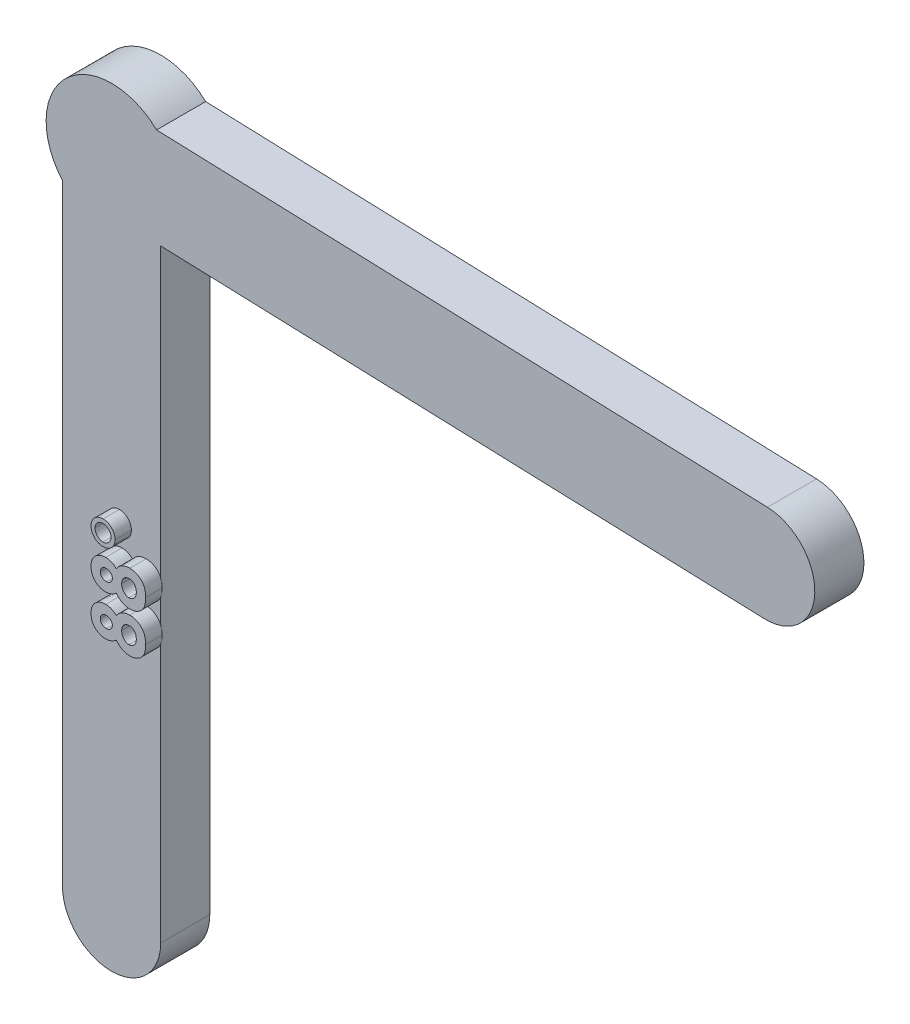
SolidWorks part; units mm, degrees
ref_plane "Front Plane" through (0, 0, 0) normal (0, 0, 1) x (1, 0, 0)
ref_plane "Top Plane" through (0, 0, 0) normal (0, 1, 0) x (1, 0, 0)
ref_plane "Right Plane" through (0, 0, 0) normal (1, 0, 0) x (0, 0, -1)
sketch "Sketch2" plane through (0, 0, 0) normal (0, 0, 1) x (1, 0, 0)
  line L0 (0, 0) -> (0, -40) construction
  line L1 (0, 0) -> (39.9756, -1.396) construction
  line L2 (40.0803, 1.6022) -> (39.8709, -4.3942) construction
  line L3 (-3, -40) -> (3, -40) construction
  line L4 (-3, -40) -> (-3, -2.6458)
  line L5 (3, -40) -> (3, -3.1066)
  line L6 (40.0803, 1.6022) -> (2.7488, 2.9058)
  line L7 (39.8709, -4.3942) -> (3, -3.1066)
  arc A0 (2.7488, 2.9058) -> (-3, -2.6458) centre (0, 0) ccw
  arc A1 (-3, -40) -> (3, -40) centre (0, -40) ccw
  arc A2 (40.0803, 1.6022) -> (39.8709, -4.3942) centre (39.9756, -1.396) cw
  point P12 (39.9756, -1.396)
  dimension "D3" = 3
  dimension "D4" = 8
  dimension "D1" = 40
  dimension "D2" = 88
extrude "Boss-Extrude1" add sketch "Sketch2" along normal blind 3
sketch "Sketch3" plane through (0, 0, 3) normal (0, 0, 1) x (1, 0, 0)
  text T0 "<b>88°</b>"
extrude "Boss-Extrude2" add sketch "Sketch3" along normal blind 1
